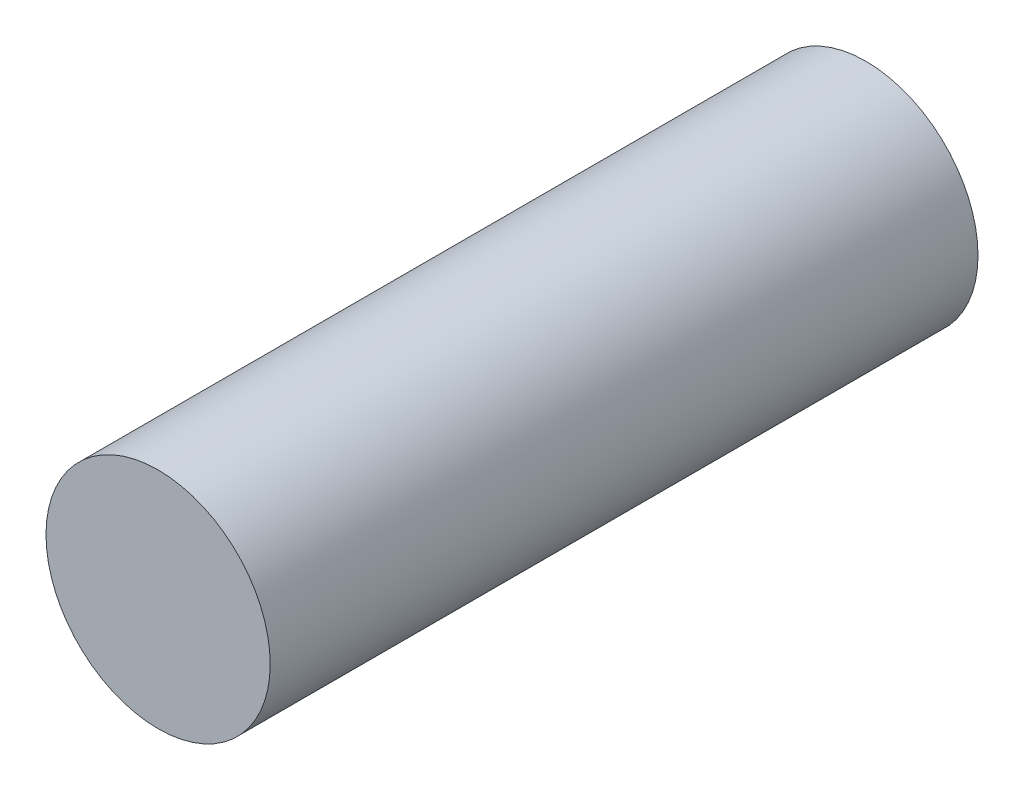
SolidWorks part; units mm, degrees
material "Acrylic (Medium-high impact)"
ref_plane "Front Plane" through (0, 0, 0) normal (0, 0, 1) x (1, 0, 0)
ref_plane "Top Plane" through (0, 0, 0) normal (0, 1, 0) x (1, 0, 0)
ref_plane "Right Plane" through (0, 0, 0) normal (1, 0, 0) x (0, 0, -1)
sketch "Sketch1" plane through (0, 0, 0) normal (0, 0, 1) x (1, 0, 0)
  circle A0 centre (81.4431, -68.4681) radius 8.89
  dimension "D1" = 17.78
extrude "Extrude1" add sketch "Sketch1" along normal up to surface (56.134 mm away)
